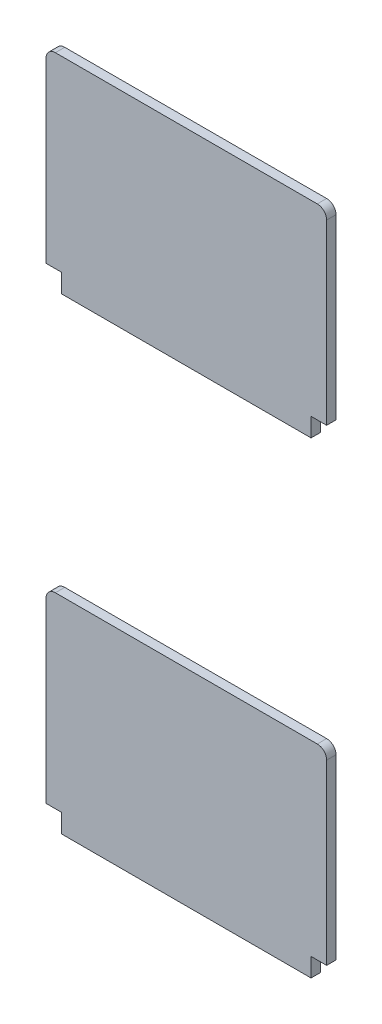
SolidWorks part; units mm, degrees
ref_plane "前基準面" through (0, 0, 0) normal (0, 0, 1) x (1, 0, 0)
ref_plane "上基準面" through (0, 0, 0) normal (0, 1, 0) x (1, 0, 0)
ref_plane "右基準面" through (0, 0, 0) normal (1, 0, 0) x (0, 0, -1)
sketch "草圖1" plane through (0, 0, 0) normal (0, 0, 1) x (1, 0, 0)
  line L0 (40, 0) -> (40, 22.084) construction
  line L1 (0, 0) -> (80, 0)
  line L2 (0, 0) -> (0, -6)
  line L3 (0, -6) -> (80, -6)
  line L4 (80, 0) -> (80, -6)
  line L5 (40, 60) -> (40, 180.9263) construction
  line L6 (-5, 0) -> (85, 0)
  line L7 (-5, 0) -> (-5, 57)
  line L8 (-2, 60) -> (82, 60)
  line L9 (85, 0) -> (85, 57)
  line L10 (0, 150) -> (0, 144)
  line L11 (0, 150) -> (80, 150)
  line L12 (80, 150) -> (80, 144)
  line L13 (0, 144) -> (80, 144)
  line L14 (-5, 150) -> (-5, 207)
  line L15 (-5, 150) -> (85, 150)
  line L16 (85, 150) -> (85, 207)
  line L17 (-2, 210) -> (82, 210)
  arc A0 (82, 60) -> (85, 57) centre (82, 57) cw
  arc A1 (-5, 57) -> (-2, 60) centre (-2, 57) cw
  arc A2 (-5, 207) -> (-2, 210) centre (-2, 207) cw
  arc A3 (82, 210) -> (85, 207) centre (82, 207) cw
  point P11 (40, 60)
  point P12 (40, -6)
  point P16 (85, 60)
  point P19 (-5, 60)
  dimension "D5" = 3
  dimension "D1" = 6
  dimension "D2" = 80
  dimension "D3" = 90
  dimension "D4" = 60
  dimension "D6" = 2
extrude "填料-伸長1" add sketch "草圖1" along normal blind 3
